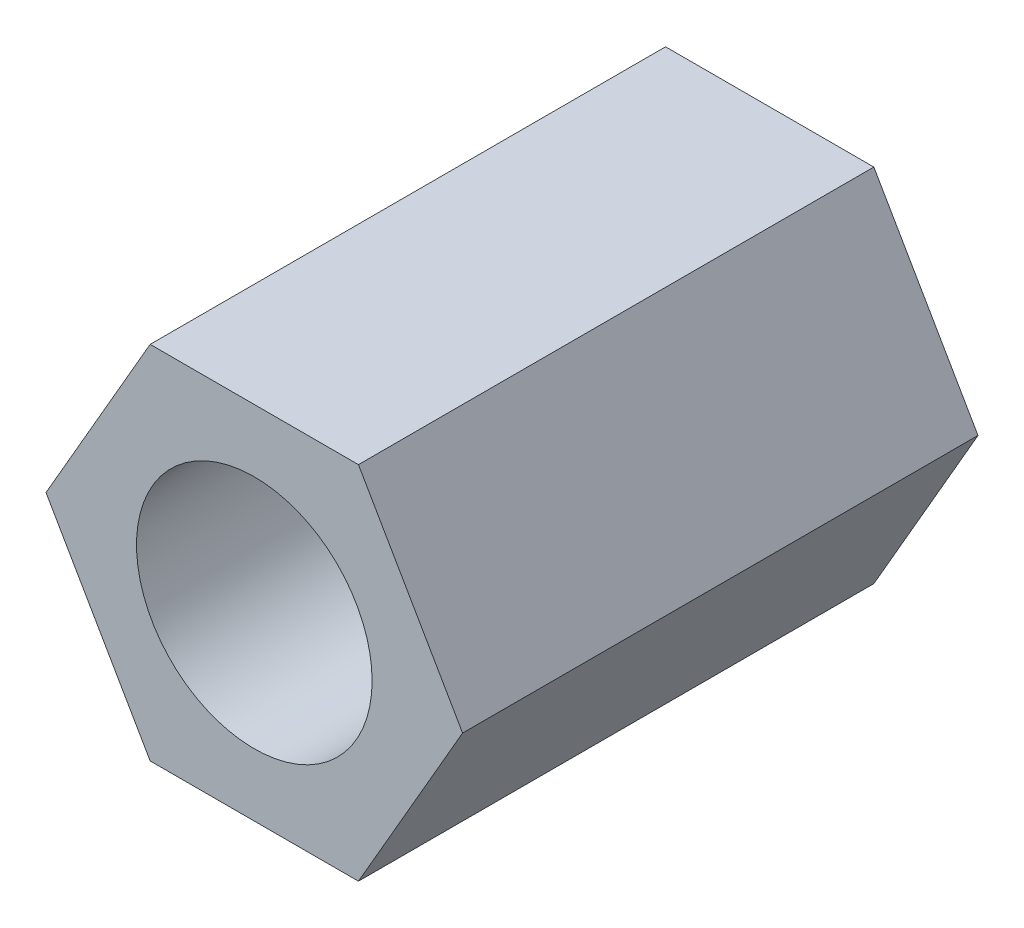
SolidWorks part; units mm, degrees
material "黄铜"
ref_plane "前视基准面" through (0, 0, 0) normal (0, 0, 1) x (1, 0, 0)
ref_plane "上视基准面" through (0, 0, 0) normal (0, 1, 0) x (1, 0, 0)
ref_plane "右视基准面" through (0, 0, 0) normal (1, 0, 0) x (0, 0, -1)
sketch "草图1" plane through (0, 0, 0) normal (0, 0, 1) x (1, 0, 0)
  line L1 (2.829, 0) -> (1.4145, 2.45)
  line L2 (1.4145, 2.45) -> (-1.4145, 2.45)
  line L3 (-1.4145, 2.45) -> (-2.829, 0)
  line L4 (-2.829, 0) -> (-1.4145, -2.45)
  line L5 (-1.4145, -2.45) -> (1.4145, -2.45)
  line L6 (1.4145, -2.45) -> (2.829, 0)
  circle A0 centre (0, 0) radius 1.6
  circle A1 centre (0, 0) radius 2.45 construction
  dimension "D1" = 3.2
  dimension "D2" = 4.9
extrude "凸台-拉伸1" add sketch "草图1" along normal blind 7
